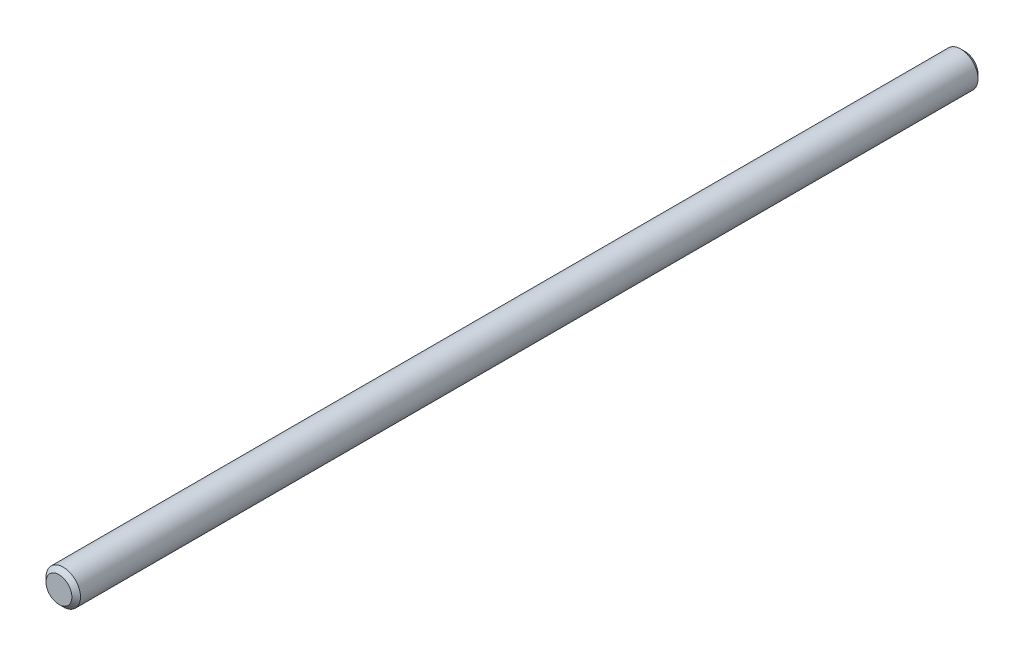
SolidWorks part; units mm, degrees
material "Slitina zinku AC41A Alloy, v odlitém stavu"
ref_plane "Přední rovina" through (0, 0, 0) normal (0, 0, 1) x (1, 0, 0)
ref_plane "Horní rovina" through (0, 0, 0) normal (0, 1, 0) x (1, 0, 0)
ref_plane "Pravá rovina" through (0, 0, 0) normal (1, 0, 0) x (0, 0, -1)
sketch "Skica1" plane through (0, 0, 0) normal (0, 0, 1) x (1, 0, 0)
  circle A0 centre (0, 0) radius 4
  dimension "D1" = 8
extrude "Přidat vysunutím1" add sketch "Skica1" along normal blind 210
chamfer "Zkosení1" distance 1 angle 45 2 edges at (4, 0, 210) (4, 0, 0)
